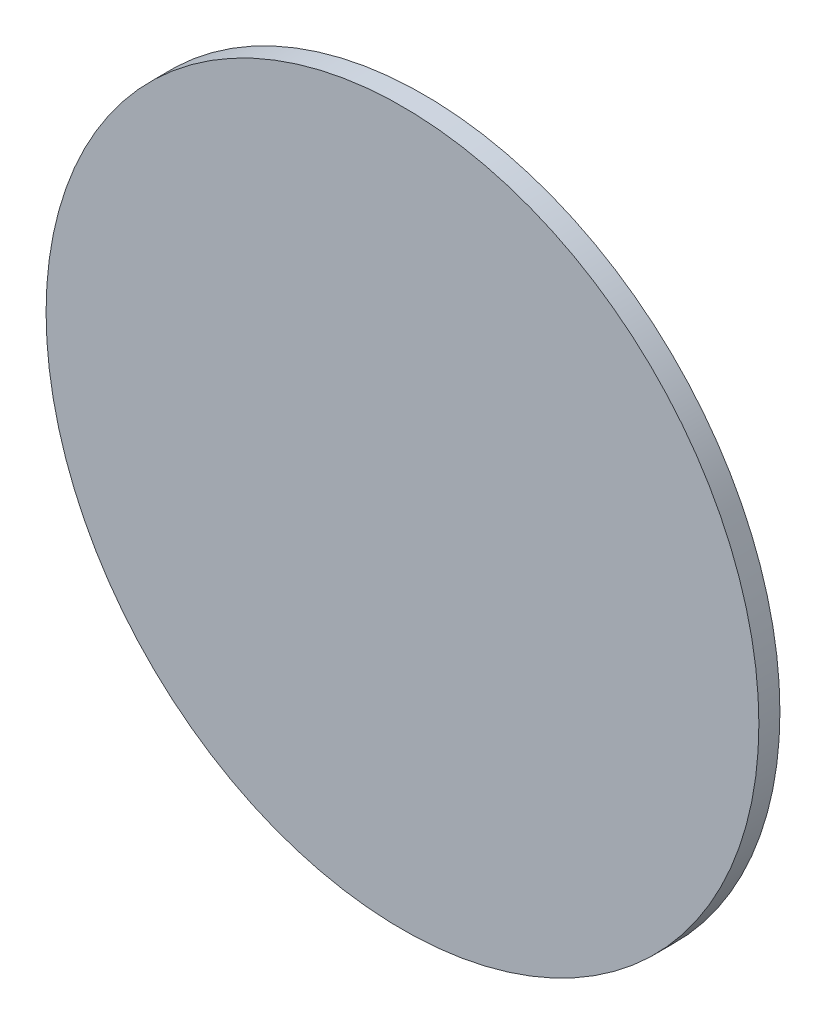
SolidWorks part; units mm, degrees
ref_plane "Front Plane" through (0, 0, 0) normal (0, 0, 1) x (1, 0, 0)
ref_plane "Top Plane" through (0, 0, 0) normal (0, 1, 0) x (1, 0, 0)
ref_plane "Right Plane" through (0, 0, 0) normal (1, 0, 0) x (0, 0, -1)
sketch "Sketch1" plane through (0, 0, 0) normal (0, 0, 1) x (1, 0, 0)
  circle A0 centre (0, 0) radius 50.8
  dimension "D1" = 101.6
extrude "Boss-Extrude1" add sketch "Sketch1" along normal blind 3
